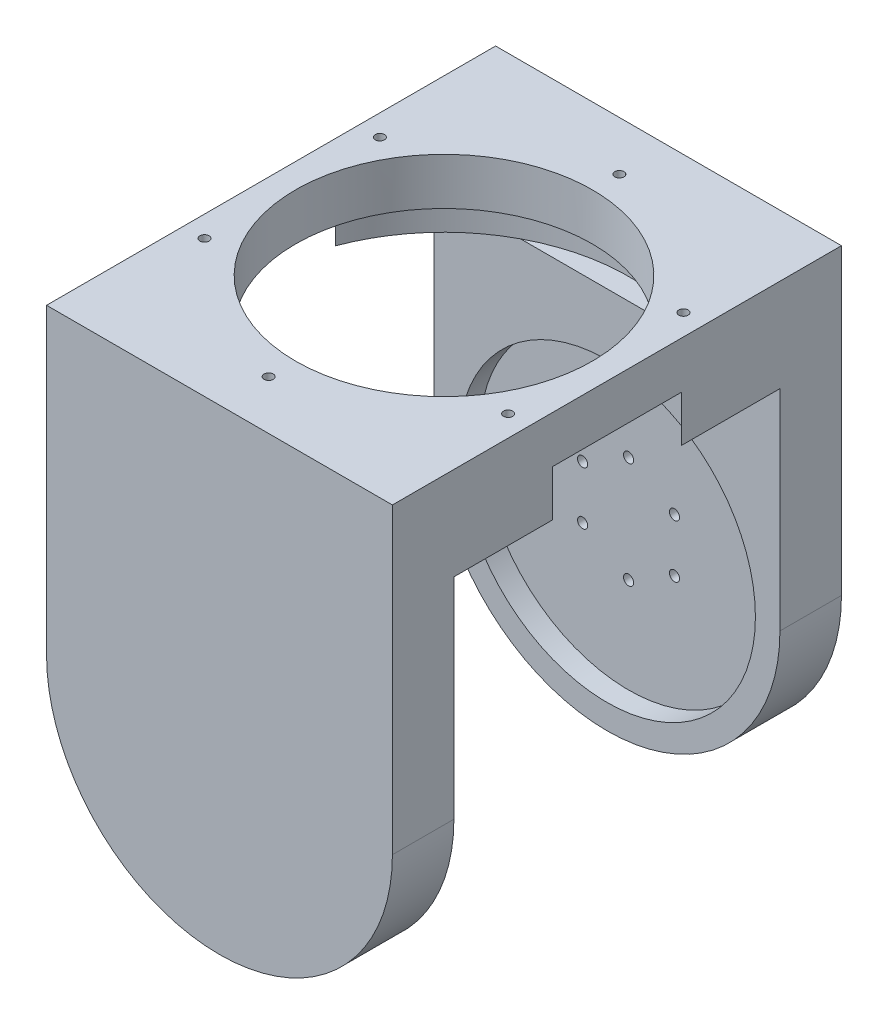
SolidWorks part; units mm, degrees
ref_plane "前视基准面" through (0, 0, 0) normal (0, 0, 1) x (1, 0, 0)
ref_plane "上视基准面" through (0, 0, 0) normal (0, 1, 0) x (1, 0, 0)
ref_plane "右视基准面" through (0, 0, 0) normal (1, 0, 0) x (0, 0, -1)
sketch "草图1" plane through (0, 0, 0) normal (0, 0, 1) x (1, 0, 0)
  line L1 (-56.2229, -36.7418) -> (56.2229, -36.7418)
  line L2 (-56.2229, -36.7418) -> (-56.2229, 36.7418)
  line L3 (-56.2229, 36.7418) -> (56.2229, 36.7418)
  line L4 (56.2229, -36.7418) -> (56.2229, 36.7418)
  line L5 (-56.2229, -36.7418) -> (56.2229, 36.7418) construction
  line L6 (-56.2229, 36.7418) -> (56.2229, -36.7418) construction
  arc A0 (-56.2229, -36.7418) -> (56.2229, -36.7418) centre (0, -36.7418) ccw
  circle A1 centre (0, -36.7418) radius 48.25
  point P0 (0, 0)
  dimension "D1" = 96.5
extrude "凸台-拉伸1" add sketch "草图1" along normal blind 20 contours A1 L1 L4 L3 L2 | A1 L1 A0
sketch "草图2" plane through (0, 0, 20) normal (0, 0, 1) x (1, 0, 0)
  line L0 (-56.2229, 18.7418) -> (56.2229, 18.7418)
  line L1 (-56.2229, 6.4938) -> (-43.9748, 18.7418)
  line L2 (-56.2229, -36.7418) -> (-56.2229, 36.7418) construction
  line L3 (56.2229, -36.7418) -> (56.2229, 36.7418)
  line L4 (56.2229, 36.7418) -> (-56.2229, 36.7418)
  line L5 (-56.2229, 36.7418) -> (-56.2229, -36.7418)
  line L6 (56.2229, 18.7418) -> (56.2229, 36.7418)
  line L7 (56.2229, 36.7418) -> (-56.2229, 36.7418)
  line L8 (-56.2229, 36.7418) -> (-56.2229, 18.7418)
  line L10 (56.2229, 6.4938) -> (43.9748, 18.7418)
  arc A1 (-56.2229, -36.7418) -> (56.2229, -36.7418) centre (0, -36.7418) ccw
  line M9 (56.2229, -36.7418) -> (56.2229, 36.7418)
  line M10 (56.2229, 36.7418) -> (-56.2229, 36.7418)
  line M11 (-56.2229, 36.7418) -> (-56.2229, -36.7418)
  dimension "D2" = 18
  dimension "D3" = 45
  dimension "D1" = 0
extrude "凸台-拉伸2" add sketch "草图2" along normal blind 66 contours L1 L0 M11 | L10 L0 M9 | L0 M11 M9 M10
sketch "草图3" plane through (0, 0, 86) normal (0, 0, 1) x (1, 0, 0)
  line L3 (-56.2229, 36.7418) -> (-56.2229, -36.7418)
  line L4 (56.2229, 36.7418) -> (-56.2229, 36.7418)
  line L5 (56.2229, -36.7418) -> (56.2229, 36.7418)
  line L6 (-56.2229, 36.7418) -> (-56.2229, -36.7418)
  line L7 (56.2229, 36.7418) -> (-56.2229, 36.7418)
  line L8 (56.2229, -36.7418) -> (56.2229, 36.7418)
  circle A0 centre (0, -36.7418) radius 48.25 construction
  arc A1 (-56.2229, -36.7418) -> (56.2229, -36.7418) centre (0, -36.7418) ccw
  arc A2 (-56.2229, -36.7418) -> (56.2229, -36.7418) centre (0, -36.7418) ccw
  circle A3 centre (0, -36.7418) radius 48.25
  dimension "D1" = 0
extrude "凸台-拉伸3" add sketch "草图3" along normal blind 20
sketch "草图4" plane through (0, 36.7418, 0) normal (0, 1, 0) x (1, 0, 0)
  line L1 (0, 0) -> (0, -4.75)
  circle A0 centre (0, -53) radius 48.25
  point P9 (0, -53)
  dimension "D2" = 96.5
extrude "切除-拉伸1" cut sketch "草图4" against normal blind 20 contours A0
sketch "草图5" plane through (0, 0, 106) normal (0, 0, 1) x (1, 0, 0)
  line L3 (56.2229, -36.7418) -> (56.2229, 36.7418)
  line L4 (56.2229, 36.7418) -> (-56.2229, 36.7418)
  line L5 (-56.2229, 36.7418) -> (-56.2229, -36.7418)
  line L6 (56.2229, -36.7418) -> (56.2229, 36.7418)
  line L7 (56.2229, 36.7418) -> (-56.2229, 36.7418)
  line L8 (-56.2229, 36.7418) -> (-56.2229, -36.7418)
  circle A0 centre (0, -36.7418) radius 48.25 construction
  arc A1 (-56.2229, -36.7418) -> (56.2229, -36.7418) centre (0, -36.7418) ccw
  arc A2 (-56.2229, -36.7418) -> (56.2229, -36.7418) centre (0, -36.7418) ccw
  circle A3 centre (0, -36.7418) radius 48.25
  dimension "D1" = 0
extrude "凸台-拉伸4" add sketch "草图5" along normal blind 20
sketch "草图6" plane through (0, 0, 86) normal (0, 0, -1) x (-1, 0, 0)
  line L9 (35.2003, 16.7418) -> (-35.2003, 16.7418)
  line L10 (-35.2003, 16.7418) -> (-35.2003, 18.7418)
  line L11 (-35.2003, 18.7418) -> (-43.9748, 18.7418)
  line L12 (-43.9748, 18.7418) -> (-56.2229, 6.4938)
  line L13 (-56.2229, 6.4938) -> (-56.2229, -36.7418)
  line L14 (56.2229, -36.7418) -> (56.2229, 6.4938)
  line L15 (56.2229, 6.4938) -> (43.9748, 18.7418)
  line L16 (43.9748, 18.7418) -> (35.2003, 18.7418)
  line L17 (35.2003, 18.7418) -> (35.2003, 16.7418)
  line L18 (35.2003, 16.7418) -> (-35.2003, 16.7418)
  line L19 (-35.2003, 16.7418) -> (-35.2003, 18.7418)
  line L20 (-35.2003, 18.7418) -> (-43.9748, 18.7418)
  line L21 (-43.9748, 18.7418) -> (-56.2229, 6.4938)
  line L22 (-56.2229, 6.4938) -> (-56.2229, -36.7418)
  line L23 (56.2229, -36.7418) -> (56.2229, 6.4938)
  line L24 (56.2229, 6.4938) -> (43.9748, 18.7418)
  line L25 (43.9748, 18.7418) -> (35.2003, 18.7418)
  line L26 (35.2003, 18.7418) -> (35.2003, 16.7418)
  arc A1 (-56.2229, -36.7418) -> (56.2229, -36.7418) centre (0, -36.7418) ccw
  arc A2 (-56.2229, -36.7418) -> (56.2229, -36.7418) centre (0, -36.7418) ccw
  dimension "D1" = 0
extrude "切除-拉伸2" cut sketch "草图6" against normal blind 20
sketch "草图7" plane through (0, 0, 0) normal (0, 0, -1) x (-1, 0, 0)
  line L3 (56.2229, -36.7418) -> (56.2229, 36.7418)
  line L4 (56.2229, 36.7418) -> (-56.2229, 36.7418)
  line L5 (-56.2229, 36.7418) -> (-56.2229, -36.7418)
  line L6 (56.2229, -36.7418) -> (56.2229, 36.7418)
  line L7 (56.2229, 36.7418) -> (-56.2229, 36.7418)
  line L8 (-56.2229, 36.7418) -> (-56.2229, -36.7418)
  circle A0 centre (0, -36.7418) radius 48.25 construction
  arc A1 (-56.2229, -36.7418) -> (56.2229, -36.7418) centre (0, -36.7418) ccw
  arc A2 (-56.2229, -36.7418) -> (56.2229, -36.7418) centre (0, -36.7418) ccw
  circle A3 centre (0, -36.7418) radius 48.25
  dimension "D1" = 0
extrude "凸台-拉伸5" add sketch "草图7" along normal blind 20
sketch "草图8" plane through (0, 0, 20) normal (0, 0, 1) x (1, 0, 0)
  line L9 (35.2003, 18.7418) -> (35.2003, 16.7418)
  line L10 (35.2003, 16.7418) -> (-35.2003, 16.7418)
  line L11 (-35.2003, 16.7418) -> (-35.2003, 18.7418)
  line L12 (-35.2003, 18.7418) -> (-43.9748, 18.7418)
  line L13 (-43.9748, 18.7418) -> (-56.2229, 6.4938)
  line L14 (-56.2229, 6.4938) -> (-56.2229, -36.7418)
  line L15 (56.2229, -36.7418) -> (56.2229, 6.4938)
  line L16 (56.2229, 6.4938) -> (43.9748, 18.7418)
  line L17 (43.9748, 18.7418) -> (35.2003, 18.7418)
  line L18 (35.2003, 18.7418) -> (35.2003, 16.7418)
  line L19 (35.2003, 16.7418) -> (-35.2003, 16.7418)
  line L20 (-35.2003, 16.7418) -> (-35.2003, 18.7418)
  line L21 (-35.2003, 18.7418) -> (-43.9748, 18.7418)
  line L22 (-43.9748, 18.7418) -> (-56.2229, 6.4938)
  line L23 (-56.2229, 6.4938) -> (-56.2229, -36.7418)
  line L24 (56.2229, -36.7418) -> (56.2229, 6.4938)
  line L25 (56.2229, 6.4938) -> (43.9748, 18.7418)
  line L26 (43.9748, 18.7418) -> (35.2003, 18.7418)
  arc A1 (-56.2229, -36.7418) -> (56.2229, -36.7418) centre (0, -36.7418) ccw
  arc A2 (-56.2229, -36.7418) -> (56.2229, -36.7418) centre (0, -36.7418) ccw
  dimension "D1" = 0
extrude "切除-拉伸3" cut sketch "草图8" against normal blind 20
sketch "草图9" plane through (0, 0, -20) normal (0, 0, -1) x (-1, 0, 0)
  circle A0 centre (0, -36.7418) radius 48.25 construction
  circle A1 centre (0, -36.7418) radius 48.25
extrude "凸台-拉伸6" add sketch "草图9" against normal blind 20
sketch "草图10" plane through (0, 0, 126) normal (0, 0, 1) x (1, 0, 0)
  circle A0 centre (0, -36.7418) radius 48.25 construction
  circle A1 centre (0, -36.7418) radius 48.25
extrude "凸台-拉伸7" add sketch "草图10" against normal blind 20
sketch "草图11" plane through (0, 0, -20) normal (0, 0, -1) x (-1, 0, 0)
  circle A0 centre (0, -36.7418) radius 17.25
  circle A1 centre (0, -19.4918) radius 1.65
  circle A2 centre (14.9389, -28.1168) radius 1.65
  circle A3 centre (14.9389, -45.3668) radius 1.65
  circle A4 centre (0, -53.9918) radius 1.65
  circle A5 centre (-14.9389, -45.3668) radius 1.65
  circle A6 centre (-14.9389, -28.1168) radius 1.65
  point P18 (0, -36.7418)
  dimension "D1" = 34.5
  dimension "D2" = 3.3
  dimension "D3" = 6
sketch "草图14" plane through (0, 0, 0) normal (0, 0, 1) x (1, 0, 0)
  circle A0 centre (-14.9389, -45.3668) radius 1.65 construction
  circle A1 centre (0, -53.9918) radius 1.65 construction
  circle A2 centre (14.9389, -45.3668) radius 1.65 construction
  circle A3 centre (14.9389, -28.1168) radius 1.65 construction
  circle A4 centre (0, -19.4918) radius 1.65 construction
  circle A5 centre (-14.9389, -28.1168) radius 1.65 construction
  circle A6 centre (-14.9389, -45.3668) radius 1.65
  circle A7 centre (0, -53.9918) radius 1.65
  circle A8 centre (14.9389, -45.3668) radius 1.65
  circle A9 centre (14.9389, -28.1168) radius 1.65
  circle A10 centre (0, -19.4918) radius 1.65
  circle A11 centre (-14.9389, -28.1168) radius 1.65
extrude "凸台-拉伸11" add sketch "草图14" along normal blind 10
sketch "草图15" plane through (0, 0, 106) normal (0, 0, -1) x (-1, 0, 0)
  circle A0 centre (14.9389, -28.1168) radius 1.65 construction
  circle A1 centre (14.9389, -45.3668) radius 1.65 construction
  circle A2 centre (0, -53.9918) radius 1.65 construction
  circle A3 centre (-14.9389, -45.3668) radius 1.65 construction
  circle A4 centre (-14.9389, -28.1168) radius 1.65 construction
  circle A5 centre (0, -19.4918) radius 1.65 construction
  circle A6 centre (14.9389, -28.1168) radius 1.65
  circle A7 centre (14.9389, -45.3668) radius 1.65
  circle A8 centre (0, -53.9918) radius 1.65
  circle A9 centre (-14.9389, -45.3668) radius 1.65
  circle A10 centre (-14.9389, -28.1168) radius 1.65
  circle A11 centre (0, -19.4918) radius 1.65
extrude "凸台-拉伸12" add sketch "草图15" along normal blind 10
sketch "草图16" plane through (0, 0, 106) normal (0, 0, -1) x (-1, 0, 0)
  circle A0 centre (0, -36.7418) radius 13.1041
  circle A1 centre (-14.9389, -45.3668) radius 1.65
  circle A3 centre (-14.9389, -45.3668) radius 1.65
  circle A4 centre (0, -53.9918) radius 1.65
  circle A5 centre (0, -53.9918) radius 1.65
  circle A6 centre (14.9389, -45.3668) radius 1.65
  circle A7 centre (14.9389, -45.3668) radius 1.65
  circle A8 centre (14.9389, -28.1168) radius 1.65
  circle A9 centre (14.9389, -28.1168) radius 1.65
  circle A10 centre (0, -19.4918) radius 1.65
  circle A11 centre (0, -19.4918) radius 1.65
  circle A12 centre (0, -36.7418) radius 27.5
  circle A14 centre (-14.9389, -28.1168) radius 1.65
  circle A15 centre (-14.9389, -28.1168) radius 1.65
  dimension "D6" = 55
  dimension "D1" = 0
  dimension "D2" = 0
  dimension "D3" = 0
  dimension "D4" = 0
  dimension "D5" = 0
  dimension "D7" = 0
extrude "凸台-拉伸13" add sketch "草图16" along normal blind 20 contours A12 | A0
sketch "草图17" plane through (0, 0, 0) normal (0, 0, 1) x (1, 0, 0)
  circle A0 centre (-14.9389, -45.3668) radius 1.65 construction
  circle A1 centre (0, -53.9918) radius 1.65 construction
  circle A2 centre (14.9389, -45.3668) radius 1.65 construction
  circle A3 centre (14.9389, -28.1168) radius 1.65 construction
  circle A4 centre (0, -19.4918) radius 1.65 construction
  circle A5 centre (-14.9389, -28.1168) radius 1.65 construction
  circle A6 centre (-14.9389, -45.3668) radius 1.65
  circle A7 centre (0, -53.9918) radius 1.65
  circle A8 centre (14.9389, -45.3668) radius 1.65
  circle A9 centre (14.9389, -28.1168) radius 1.65
  circle A10 centre (0, -19.4918) radius 1.65
  circle A11 centre (-14.9389, -28.1168) radius 1.65
extrude "切除-拉伸4" cut sketch "草图17" against normal up to next and the other way up to next
sketch "草图18" plane through (0, 0, 0) normal (0, 0, 1) x (1, 0, 0)
  circle A1 centre (0, -36.7418) radius 48.25
  circle A2 centre (0, -36.7418) radius 48.25
  dimension "D1" = 0
extrude "切除-拉伸5" cut sketch "草图18" against normal blind 7
sketch "草图19" plane through (-56.2229, 0, 0) normal (-1, 0, 0) x (0, 0, 1)
  line L0 (106, 18.7418) -> (106, 31.4938)
  line L1 (106, 31.4938) -> (0, 31.4938)
  line L2 (0, 31.4938) -> (0, 18.7418)
  line L6 (33.1436, 18.7418) -> (0, 18.7418)
  line L7 (0, 18.7418) -> (0, 6.4938)
  line L8 (0, -36.7418) -> (0, 6.4938)
  line L9 (0, 6.4938) -> (106, 6.4938)
  line L10 (106, 6.4938) -> (106, -36.7418)
  line L11 (106, -36.7418) -> (126, -36.7418)
  line L12 (126, -36.7418) -> (126, 36.7418)
  line L13 (126, 36.7418) -> (-20, 36.7418)
  line L14 (-20, 36.7418) -> (-20, -36.7418)
  line L15 (-20, -36.7418) -> (0, -36.7418)
  line L17 (0, 6.4938) -> (106, 6.4938)
  line L24 (0, 6.4938) -> (106, 6.4938)
  line L25 (106, 6.4938) -> (106, 18.7418)
  line L26 (106, 18.7418) -> (72.8564, 18.7418)
  line L27 (67.6416, 16.7418) -> (38.3584, 16.7418)
  line L29 (0, 18.7418) -> (0, 6.4938)
  line L30 (0, 6.4938) -> (106, 6.4938)
  line L31 (106, 6.4938) -> (106, 18.7418)
  arc A2 (33.1436, 18.7418) -> (38.3584, 16.7418) centre (53, 62.7167) ccw
  arc A3 (67.6416, 16.7418) -> (72.8564, 18.7418) centre (53, 62.7167) ccw
  line M19 (0, 6.4938) -> (106, 6.4938)
  dimension "D3" = 25
  dimension "D1" = 0
  dimension "D2" = 0
extrude "切除-拉伸6" cut sketch "草图19" against normal through all contours L31 L0 L1 L2 L29 M19
sketch "草图20" plane through (0, 36.7418, 0) normal (0, 1, 0) x (1, 0, 0)
  line L4 (56.2229, -126) -> (56.2229, 20)
  line L5 (56.2229, 20) -> (-56.2229, 20)
  line L6 (-56.2229, 20) -> (-56.2229, -126)
  line L7 (-56.2229, -126) -> (56.2229, -126)
  line L8 (56.2229, -126) -> (56.2229, 20)
  line L9 (56.2229, 20) -> (-56.2229, 20)
  line L10 (-56.2229, 20) -> (-56.2229, -126)
  line L11 (-56.2229, -126) -> (56.2229, -126)
  circle A0 centre (0, -53) radius 48.25 construction
  circle A1 centre (0, -53) radius 48.25
  dimension "D1" = 0
extrude "凸台-拉伸14" add sketch "草图20" along normal blind 25 contours L8 L9 L10 L11
sketch "草图21" plane through (0, 31.4938, 0) normal (0, -1, 0) x (1, 0, 0)
  circle A0 centre (0, 53) radius 60
  dimension "D2" = 120
extrude "切除-拉伸7" cut sketch "草图21" against normal blind 15
sketch "草图22" plane through (0, 46.4938, 0) normal (0, -1, 0) x (1, 0, 0)
  circle A1 centre (0, 110) radius 1.5
  circle A6 centre (49.3634, 81.5) radius 1.5
  circle A7 centre (49.3634, 24.5) radius 1.5
  circle A8 centre (0, -4) radius 1.5
  circle A9 centre (-49.3634, 24.5) radius 1.5
  circle A10 centre (-49.3634, 81.5) radius 1.5
  point P22 (0, 53)
  dimension "D3" = 3
  dimension "D4" = 6
extrude "切除-拉伸8" cut sketch "草图22" against normal through all
